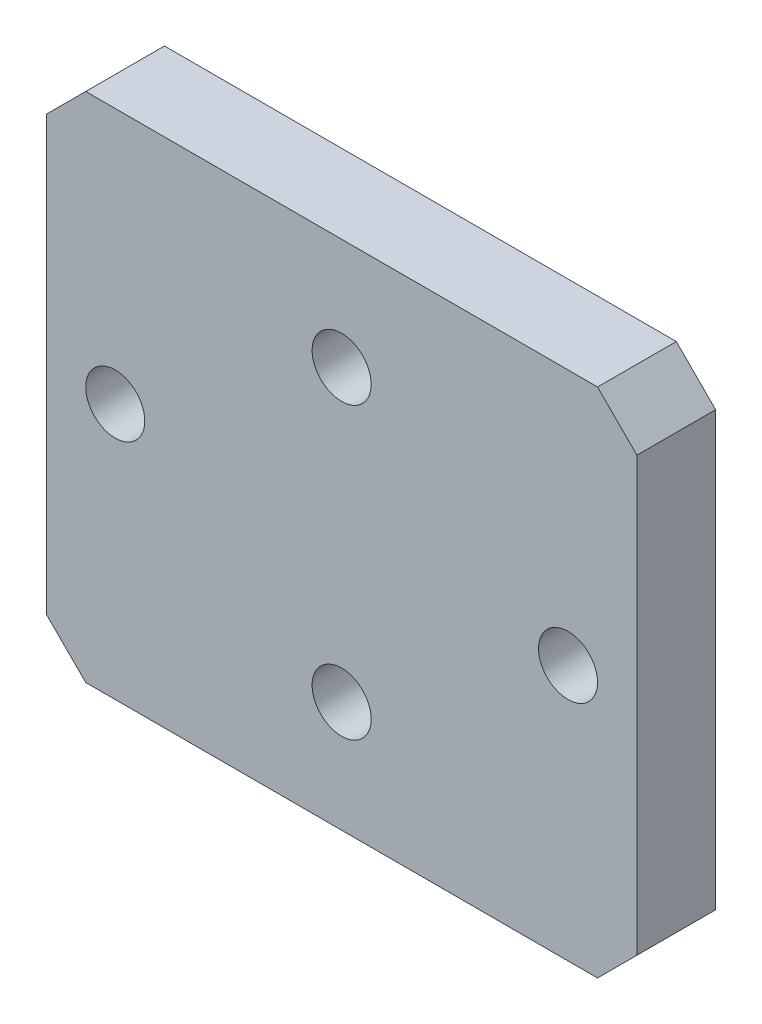
SolidWorks part; units mm, degrees
ref_plane "Plan de face" through (0, 0, 0) normal (0, 0, 1) x (1, 0, 0)
ref_plane "Plan de dessus" through (0, 0, 0) normal (0, 1, 0) x (1, 0, 0)
ref_plane "Plan de droite" through (0, 0, 0) normal (1, 0, 0) x (0, 0, -1)
sketch "Sketch1" plane through (0, 0, 0) normal (0, 0, 1) x (1, 0, 0)
  line L0 (0, 24) -> (2, 26)
  line L1 (2, 0) -> (28, 0)
  line L2 (0, 2) -> (0, 24)
  line L3 (2, 26) -> (28, 26)
  line L4 (30, 2) -> (30, 24)
  line L5 (28, 26) -> (30, 24)
  line L6 (28, 0) -> (30, 2)
  line L7 (0, 2) -> (2, 0)
  line L8 (3.5, 13) -> (26.5, 13) construction
  line L9 (15, 5.635) -> (15, 20.365) construction
  circle A0 centre (3.5, 13) radius 1.5
  circle A1 centre (26.5, 13) radius 1.5
  circle A2 centre (15, 20.365) radius 1.5
  circle A3 centre (15, 5.635) radius 1.5
  point P0 (0, 0)
  point P1 (30, 26)
  point P2 (0, 26)
  point P3 (30, 0)
  point P17 (15, 13)
  point P18 (0, 13)
  point P19 (15, 26)
  point P25 (15, 13)
  dimension "D4" = 3
  dimension "D9" = 3
  dimension "D10" = 3
  dimension "D1" = 26
  dimension "D2" = 30
  dimension "D3" = 23
  dimension "D11" = 14.73
extrude "Boss-Extrude1" add sketch "Sketch1" along normal blind 4
ref_plane "Plan1" through (15, 0, 0) normal (1, 0, 0) x (0, 0, -1)
